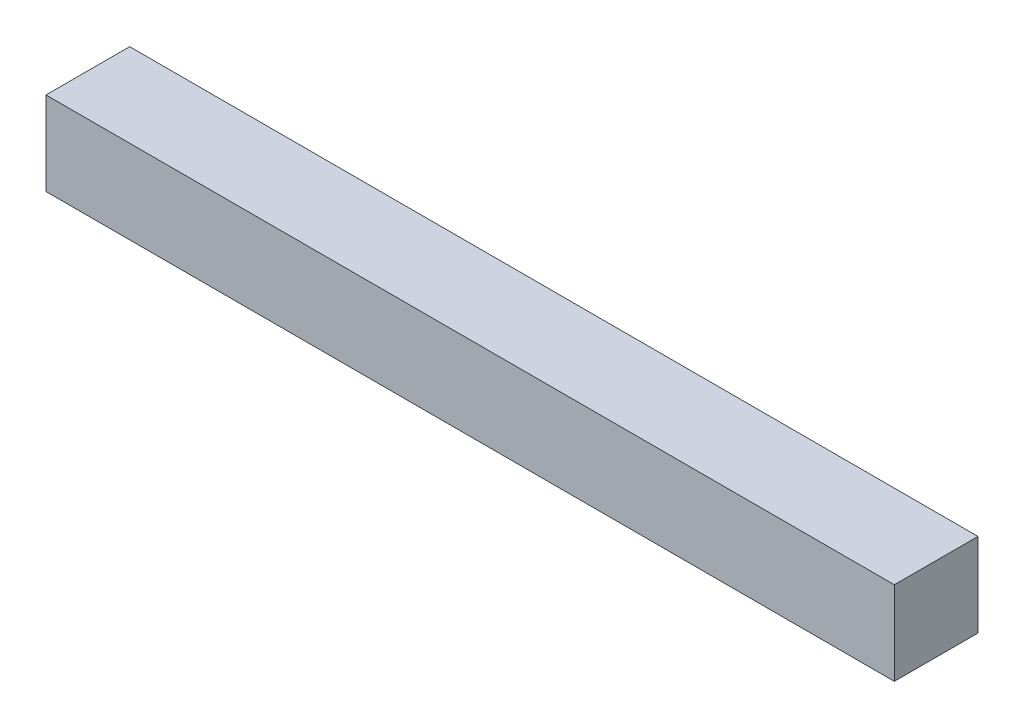
SolidWorks part; units mm, degrees
ref_plane "Front Plane" through (0, 0, 0) normal (0, 0, 1) x (1, 0, 0)
ref_plane "Top Plane" through (0, 0, 0) normal (0, 1, 0) x (1, 0, 0)
ref_plane "Right Plane" through (0, 0, 0) normal (1, 0, 0) x (0, 0, -1)
ref_plane "Plane1" through (0, 0, 1) normal (0, 0, 1) x (1, 0, 0)
sketch "Sketch2" plane through (0, 0, 1) normal (0, 0, 1) x (1, 0, 0)
  line L0 (25.35, 9) -> (25.35, 14) construction
  line L1 (-25.35, 9) -> (25.35, 9) construction
  line L2 (25.35, 14) -> (-25.35, 14) construction
  line L3 (-25.35, 14) -> (-25.35, 9) construction
  line L4 (25.35, 9) -> (25.35, 14)
  line L5 (-25.35, 9) -> (25.35, 9)
  line L6 (25.35, 14) -> (-25.35, 14)
  line L7 (-25.35, 14) -> (-25.35, 9)
extrude "Boss-Extrude1" add sketch "Sketch2" along normal blind 5
